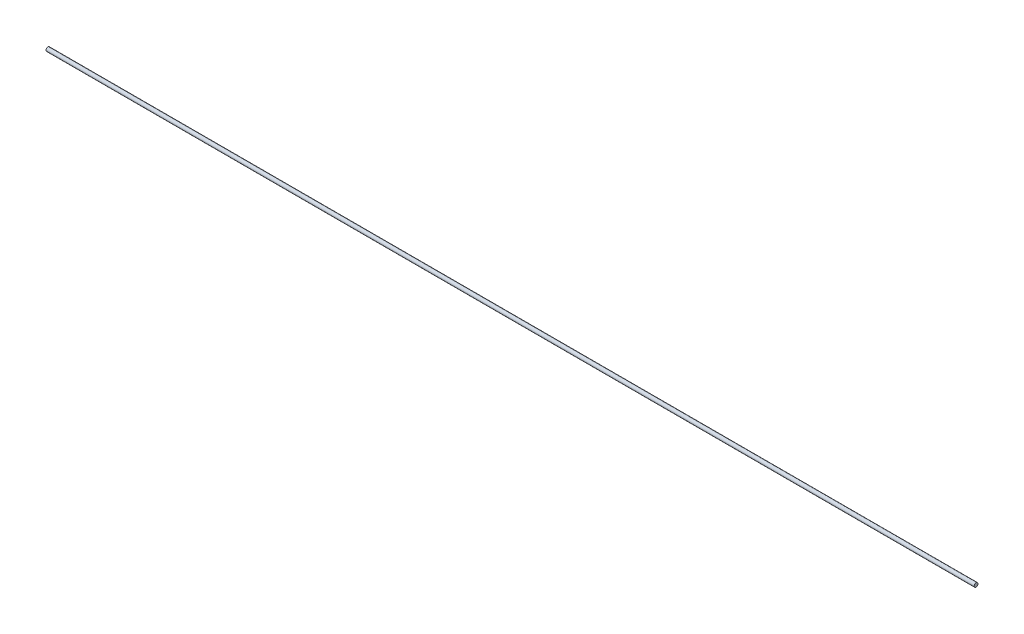
SolidWorks part; units mm, degrees
ref_plane "Спереди" through (0, 0, 0) normal (0, 0, 1) x (1, 0, 0)
ref_plane "Сверху" through (0, 0, 0) normal (0, 1, 0) x (1, 0, 0)
ref_plane "Справа" through (0, 0, 0) normal (1, 0, 0) x (0, 0, -1)
sketch "Эскиз1" plane through (0, 0, 0) normal (1, 0, 0) x (0, 0, -1)
  circle A0 centre (0, 0) radius 0.415
extrude "Вытянуть1" add sketch "Эскиз1" along normal blind 200
